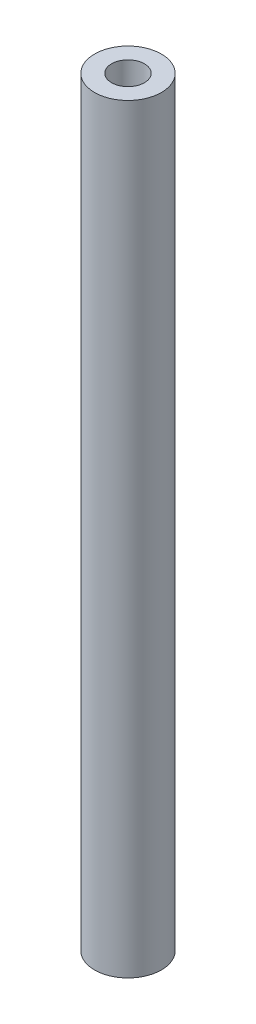
SolidWorks part; units mm, degrees
ref_plane "Front Plane" through (0, 0, 0) normal (0, 0, 1) x (1, 0, 0)
ref_plane "Top Plane" through (0, 0, 0) normal (0, 1, 0) x (1, 0, 0)
ref_plane "Right Plane" through (0, 0, 0) normal (1, 0, 0) x (0, 0, -1)
sketch "Sketch1" plane through (0, 0, 0) normal (0, 1, 0) x (1, 0, 0)
  circle A0 centre (0, 0) radius 3.25
  circle A1 centre (0, 0) radius 1.6
  dimension "D1" = 3.2
  dimension "D2" = 6.5
extrude "Boss-Extrude1" add sketch "Sketch1" along normal blind 74
